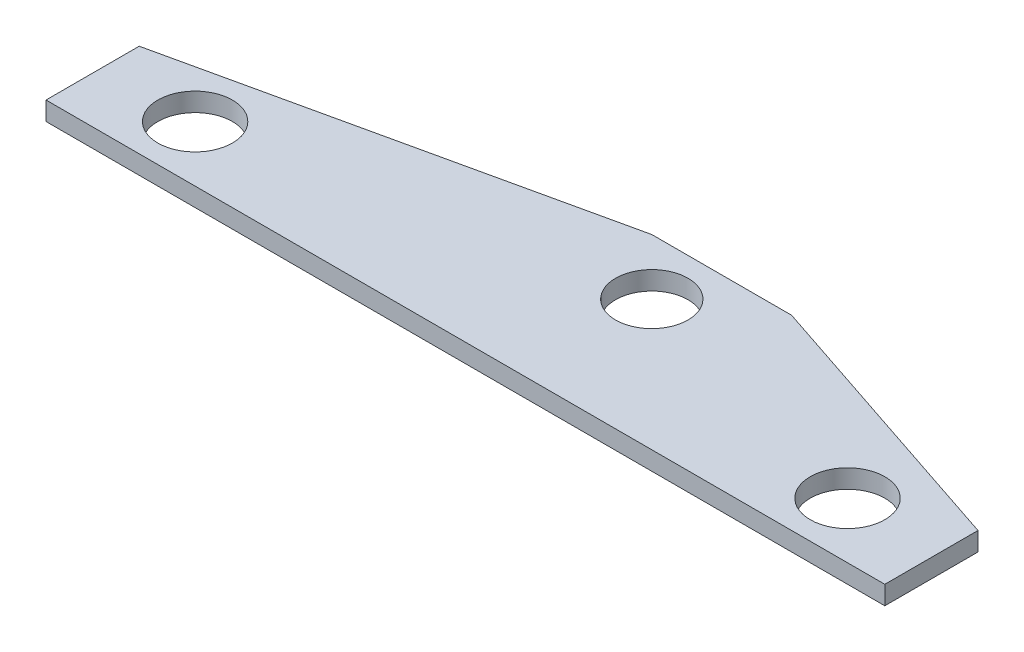
SolidWorks part; units mm, degrees
ref_plane "Front Plane" through (0, 0, 0) normal (0, 0, 1) x (1, 0, 0)
ref_plane "Top Plane" through (0, 0, 0) normal (0, 1, 0) x (1, 0, 0)
ref_plane "Right Plane" through (0, 0, 0) normal (1, 0, 0) x (0, 0, -1)
sketch "Sketch1" plane through (0, 0, 0) normal (0, 1, 0) x (1, 0, 0)
  line L1 (0, 0) -> (90, 0)
  line L2 (0, 0) -> (0, 20)
  line L3 (0, 20) -> (90, 20)
  line L4 (90, 0) -> (90, 20)
  dimension "D1" = 90
  dimension "D2" = 20
extrude "Boss-Extrude1" add sketch "Sketch1" along normal blind 2
sketch "Sketch2" plane through (0, 2, 0) normal (0, 1, 0) x (1, 0, 0)
  line L0 (0, 0) -> (90, 0) construction
  line L1 (45, 20) -> (45, 0)
  line L2 (90, 20) -> (0, 20) construction
  line L3 (0, 10) -> (45, 20)
  line L4 (0, 20) -> (0, 0) construction
  line L5 (60, 20) -> (90, 10)
  line L6 (90, 0) -> (90, 20) construction
  line L7 (0, 10) -> (0, 20)
  line L8 (0, 20) -> (45, 20)
  line L9 (90, 10) -> (90, 20)
  line L10 (90, 20) -> (60, 20)
  line L11 (45, 20) -> (60, 20)
  circle A0 centre (10, 6) radius 4
  circle A1 centre (80, 6) radius 4
  circle A2 centre (51, 14) radius 3.8832
  point P12 (60, 20)
  point P13 (45, 20)
  line M4 (0, 20) -> (0, 0)
  line M6 (90, 0) -> (90, 20)
  line M7 (90, 20) -> (0, 20)
  dimension "D1" = 8
  dimension "D2" = 6
  dimension "D3" = 35
  dimension "D4" = 6
  dimension "D5" = 6
extrude "Cut-Extrude1" cut sketch "Sketch2" against normal blind 2 contours A0 | A2 | A1 | L3 M4 M7 | L5 M7 M6
ref_plane "Plane1" through (0, 2, 0) normal (0, 0, 1) x (1, 0, 0)
